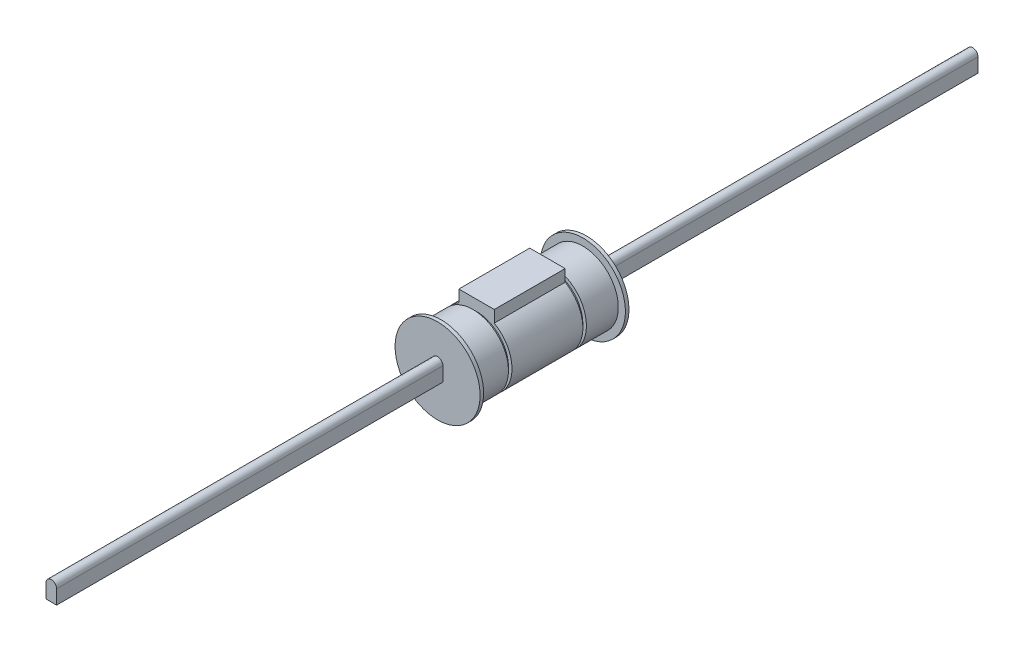
SolidWorks part; units mm, degrees
ref_plane "Front Plane" through (0, 0, 0) normal (0, 0, 1) x (1, 0, 0)
ref_plane "Top Plane" through (0, 0, 0) normal (0, 1, 0) x (1, 0, 0)
ref_plane "Right Plane" through (0, 0, 0) normal (1, 0, 0) x (0, 0, -1)
sketch "Sketch1" plane through (0, 0, 0) normal (0, 0, 1) x (1, 0, 0)
  line L5 (0.75, -1) -> (-0.75, -1)
  line L6 (0.75, -1) -> (0.75, 1)
  line L7 (0.75, 1) -> (-0.75, 1)
  line L8 (-0.75, -1) -> (-0.75, 1)
  line L9 (0.75, -1) -> (-0.75, 1) construction
  line L10 (0.75, 1) -> (-0.75, -1) construction
  circle A2 centre (0, 1) radius 0.75
  point P0 (0, 0)
  point P1 (0, 0)
  dimension "D1" = 1.5
  dimension "D2" = 2
extrude "Boss-Extrude4" add sketch "Sketch1" along normal blind 55 contours L7 A2 | A2 L8 L5 L6
sketch "Sketch4" plane through (0, 0, 55) normal (0, 0, 1) x (1, 0, 0)
  circle A0 centre (0, 0) radius 5
  dimension "D1" = 10
extrude "Boss-Extrude5" add sketch "Sketch4" along normal blind 5
sketch "Sketch5" plane through (0, 0, 60) normal (0, 0, 1) x (1, 0, 0)
  line L1 (2.5, 4) -> (-2.5, 4)
  line L2 (2.5, 4) -> (2.5, 6)
  line L3 (2.5, 6) -> (-2.5, 6)
  line L4 (-2.5, 4) -> (-2.5, 6)
  line L5 (2.5, 4) -> (-2.5, 6) construction
  line L6 (2.5, 6) -> (-2.5, 4) construction
  circle A0 centre (0, 0) radius 5
  point P3 (0, 5)
  circle M4 centre (0, 0) radius 5
  dimension "D2" = 10
  dimension "D1" = 5
  dimension "D3" = 2
extrude "Boss-Extrude6" add sketch "Sketch5" along normal blind 10 contours L1 L4 L2 M4 | L4 L1 L2 M4 | L4 L2 L3 M4
sketch "Sketch6" plane through (0, 0, 70) normal (0, 0, 1) x (1, 0, 0)
  circle A0 centre (0, 0) radius 5
extrude "Boss-Extrude7" add sketch "Sketch6" along normal blind 5
sketch "Sketch7" plane through (0, 0, 75) normal (0, 0, 1) x (1, 0, 0)
  line L1 (0.75, -1) -> (-0.75, -1)
  line L2 (0.75, -1) -> (0.75, 1)
  line L3 (0.75, 1) -> (-0.75, 1)
  line L4 (-0.75, -1) -> (-0.75, 1)
  line L5 (0.75, -1) -> (-0.75, 1) construction
  line L6 (0.75, 1) -> (-0.75, -1) construction
  circle A0 centre (0, 1) radius 0.75
  point P0 (0, 0)
  dimension "D1" = 2
  dimension "D2" = 1.5
extrude "Boss-Extrude8" add sketch "Sketch7" along normal blind 55 contours L3 A0 | L3 A0 | A0 L4 L1 L2
ref_plane "Plane1" through (0, 0, 60) normal (0, 0, 1) x (1, 0, 0)
sketch "Sketch8" plane through (0, 0, 60) normal (0, 0, 1) x (1, 0, 0)
  circle A0 centre (0, 0) radius 4.5
  circle A1 centre (0, 0) radius 5
  dimension "D1" = 9
  dimension "D2" = 10
extrude "Cut-Extrude2" cut sketch "Sketch8" against normal blind 0.5
ref_plane "Plane2" through (0, 0, 65) normal (0, 0, 1) x (1, 0, 0)
mirror "Mirror3" about plane through (0, 0, 65) normal (0, 0, 1) of "Cut-Extrude2"
sketch "Sketch9" plane through (0, 0, 55) normal (0, 0, -1) x (-1, 0, 0)
  circle A0 centre (0, 0) radius 6
  dimension "D1" = 12
extrude "Boss-Extrude9" add sketch "Sketch9" along normal blind 0.5
mirror "Mirror4" about plane through (0, 0, 65) normal (0, 0, 1) of "Boss-Extrude9"
